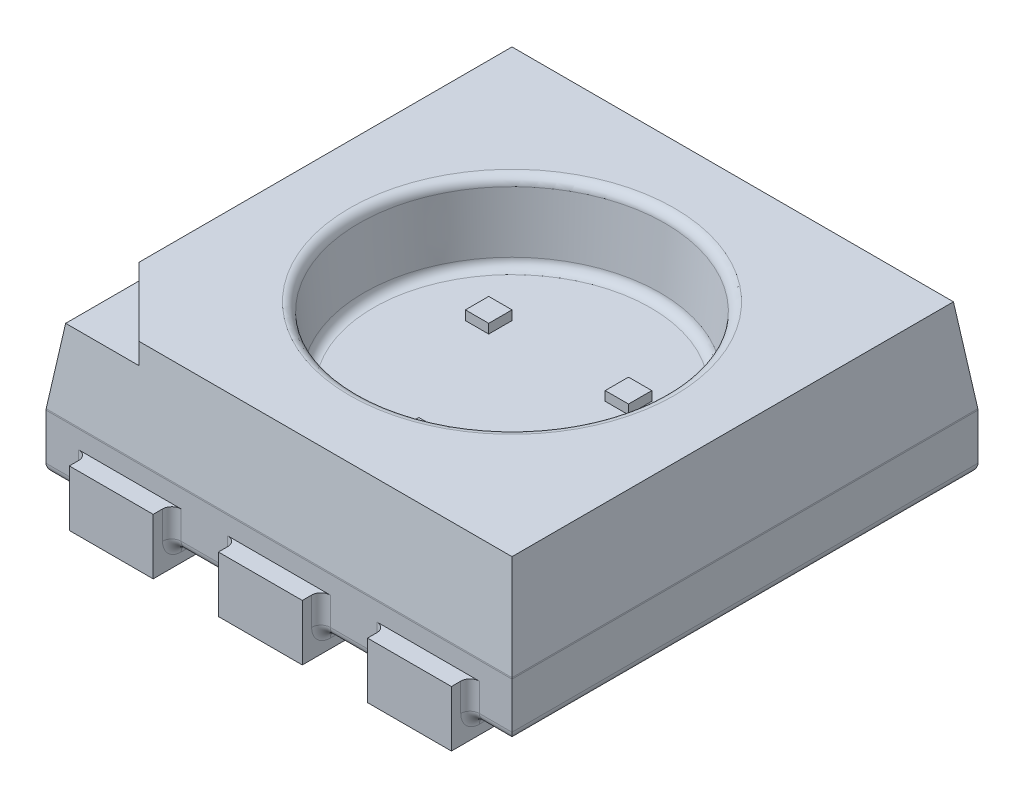
SolidWorks part; units mm, degrees
ref_plane "Front Plane" through (0, 0, 0) normal (0, 0, 1) x (1, 0, 0)
ref_plane "Top Plane" through (0, 0, 0) normal (0, 1, 0) x (1, 0, 0)
ref_plane "Right Plane" through (0, 0, 0) normal (1, 0, 0) x (0, 0, -1)
sketch "Sketch1" plane through (0, 0, 0) normal (0, 1, 0) x (1, 0, 0)
  line L1 (-2.5, 2.5) -> (2.5, 2.5)
  line L2 (-2.5, 2.5) -> (-2.5, -2.5)
  line L3 (-2.5, -2.5) -> (2.5, -2.5)
  line L4 (2.5, 2.5) -> (2.5, -2.5)
  line L5 (-2.5, 2.5) -> (2.5, -2.5) construction
  line L6 (-2.5, -2.5) -> (2.5, 2.5) construction
  point P0 (0, 0)
  dimension "D1" = 5
extrude "Boss-Extrude1" add sketch "Sketch1" along normal mid plane 1.6
sketch "Sketch2" plane through (0, -0.8, 0) normal (0, -1, 0) x (1, 0, 0)
  line L0 (0, 3.0343) -> (0, -3.2829) construction
  line L1 (-3.1068, 0) -> (2.8169, 0) construction
  line L2 (-2.5, 2.5) -> (2.5, 2.5) construction
  line L3 (-2.05, 2.7) -> (-1.15, 2.7)
  line L4 (-2.05, 2.7) -> (-2.05, 1.7)
  line L5 (-2.05, 1.7) -> (-1.15, 1.7)
  line L6 (-1.15, 2.7) -> (-1.15, 1.7)
  line L7 (-2.05, 2.7) -> (-1.15, 1.7) construction
  line L8 (-2.05, 1.7) -> (-1.15, 2.7) construction
  line L9 (2.05, 1.7) -> (1.15, 1.7)
  line L10 (-0.45, 2.7) -> (0.45, 2.7)
  line L11 (-0.45, 2.7) -> (-0.45, 1.7)
  line L12 (-0.45, 1.7) -> (0.45, 1.7)
  line L13 (0.45, 2.7) -> (0.45, 1.7)
  line L14 (-0.45, 2.7) -> (0.45, 1.7) construction
  line L15 (-0.45, 1.7) -> (0.45, 2.7) construction
  line L16 (1.15, 2.7) -> (1.15, 1.7)
  line L17 (2.05, 2.7) -> (1.15, 2.7)
  line L18 (2.05, 2.7) -> (2.05, 1.7)
  line L19 (2.05, -2.7) -> (2.05, -1.7)
  line L20 (2.05, -2.7) -> (1.15, -2.7)
  line L21 (1.15, -2.7) -> (1.15, -1.7)
  line L22 (2.05, -1.7) -> (1.15, -1.7)
  line L23 (-0.45, -1.7) -> (0.45, -1.7)
  line L24 (0.45, -2.7) -> (0.45, -1.7)
  line L25 (-0.45, -2.7) -> (0.45, -2.7)
  line L26 (-0.45, -2.7) -> (-0.45, -1.7)
  line L27 (-2.05, -1.7) -> (-1.15, -1.7)
  line L28 (-1.15, -2.7) -> (-1.15, -1.7)
  line L29 (-2.05, -2.7) -> (-1.15, -2.7)
  line L30 (-2.05, -2.7) -> (-2.05, -1.7)
  point P5 (-1.33, 2.5)
  point P12 (0, 2.2)
  point P21 (0, 0)
  point P22 (0, 0)
  point P23 (0, 0)
  point P24 (-1.6, 2.5)
  dimension "D1" = 0.9
  dimension "D2" = 2.3
  dimension "D3" = 4.1
  dimension "D4" = 3.4
  dimension "D5" = 5.4
extrude "Boss-Extrude2" add sketch "Sketch2" along normal blind 0.2 and the other way blind 0.4
chamfer "Chamfer1" distance 1 angle 7.5 4 edges at (0, 0.8, 2.5) (-2.5, 0.8, 0) (0, 0.8, -2.5) (2.5, 0.8, 0)
sketch "Sketch3" plane through (0, 0.8, 0) normal (0, 1, 0) x (1, 0, 0)
  line L0 (-2.5, -1.5) -> (-1.5, -2.5)
  line L1 (-2.5, -2.5) -> (-2.5, 2.5) construction
  line L2 (2.5, -2.5) -> (-2.5, -2.5) construction
  line L3 (-1.5, -2.5) -> (-2.5, -2.5)
  line L4 (-2.5, -2.5) -> (-2.5, -1.5)
  dimension "D1" = 1
extrude "Cut-Extrude1" cut sketch "Sketch3" against normal blind 0.2
sketch "Sketch4" plane through (0, 0.8, 0) normal (0, 1, 0) x (1, 0, 0)
  circle A0 centre (0, 0) radius 1.65
  dimension "D1" = 3.3
extrude "Cut-Extrude2" cut sketch "Sketch4" against normal blind 0.8 draft 5
fillet "Fillet1" radius 0.1 46 edges at (-2.05, -0.6, 2.5) (-1.15, -0.6, 2.5) (-0.45, -0.6, 2.5) (0.45, -0.6, 2.5) (1.15, -0.6, 2.5) (2.05, -0.6, 2.5) (2.05, -0.6, -2.5) (1.15, -0.6, -2.5) (0.45, -0.6, -2.5) (-0.45, -0.6, -2.5) (-1.15, -0.6, -2.5) (-2.05, -0.6, -2.5) (-2.5, -0.8, 0) (-2.275, -0.8, 2.5) (-2.05, -0.8, 2.1) (-1.6, -0.8, 1.7) (-1.15, -0.8, 2.1) (-0.8, -0.8, 2.5) (-0.45, -0.8, 2.1) (0, -0.8, 1.7) (0.45, -0.8, 2.1) (0.8, -0.8, 2.5) (1.15, -0.8, 2.1) (1.6, -0.8, 1.7) (2.05, -0.8, 2.1) (2.275, -0.8, 2.5) (2.5, -0.8, 0) (2.275, -0.8, -2.5) (2.05, -0.8, -2.1) (1.6, -0.8, -1.7) (1.15, -0.8, -2.1) (0.8, -0.8, -2.5) (0.45, -0.8, -2.1) (0, -0.8, -1.7) (-0.45, -0.8, -2.1) (-0.8, -0.8, -2.5) (-1.15, -0.8, -2.1) (-1.6, -0.8, -1.7) (-2.05, -0.8, -2.1) (-2.275, -0.8, -2.5) (0, -0.2, -2.5) (2.5, -0.2, 0) (0, -0.2, 2.5) (-2.5, -0.2, 0) (0, 0.8, 1.65) (0, 0, 1.58)
sketch "Sketch5" plane through (0, 0, 0) normal (0, 1, 0) x (1, 0, 0)
  line L0 (0, 0) -> (0, 1.4884) construction
  line L1 (-0.875, 0.625) -> (-0.625, 0.625)
  line L2 (-0.875, 0.625) -> (-0.875, 0.375)
  line L3 (-0.875, 0.375) -> (-0.625, 0.375)
  line L4 (-0.625, 0.625) -> (-0.625, 0.375)
  line L5 (-0.875, 0.625) -> (-0.625, 0.375) construction
  line L6 (-0.875, 0.375) -> (-0.625, 0.625) construction
  line L7 (-0.125, -0.875) -> (0.125, -0.875)
  line L8 (-0.125, -0.875) -> (-0.125, -1.125)
  line L9 (-0.125, -1.125) -> (0.125, -1.125)
  line L10 (0.125, -0.875) -> (0.125, -1.125)
  line L11 (-0.125, -0.875) -> (0.125, -1.125) construction
  line L12 (-0.125, -1.125) -> (0.125, -0.875) construction
  line L17 (0.875, 0.375) -> (0.625, 0.625) construction
  line L18 (0.875, 0.625) -> (0.625, 0.375) construction
  line L19 (0.625, 0.625) -> (0.625, 0.375)
  line L20 (0.875, 0.375) -> (0.625, 0.375)
  line L21 (0.875, 0.625) -> (0.875, 0.375)
  line L22 (0.875, 0.625) -> (0.625, 0.625)
  circle A0 centre (0, 0) radius 1.4884 construction
  point P0 (-0.75, 0.5)
  point P5 (0, -1)
  point P14 (0.75, 0.5)
  point P21 (0, 0)
  point P22 (0.125, -0.7456)
  dimension "D1" = 1.5
  dimension "D2" = 0.25
  dimension "D3" = 1.5
  dimension "D4" = 0.5
extrude "Boss-Extrude4" add sketch "Sketch5" along normal blind 0.1 separate body
